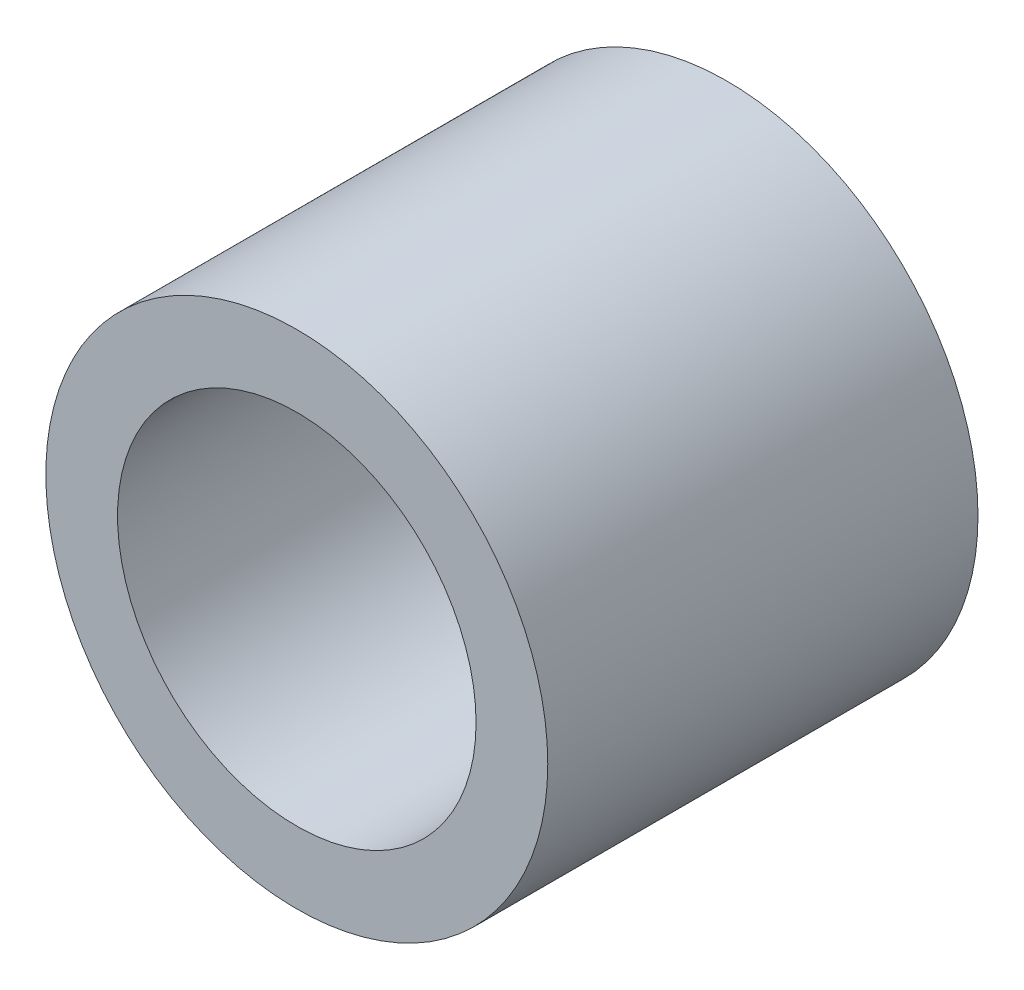
SolidWorks part; units mm, degrees
ref_plane "前视基准面" through (0, 0, 0) normal (0, 0, 1) x (1, 0, 0)
ref_plane "上视基准面" through (0, 0, 0) normal (0, 1, 0) x (1, 0, 0)
ref_plane "右视基准面" through (0, 0, 0) normal (1, 0, 0) x (0, 0, -1)
other "Configuration Table"
sketch "草图1" plane through (0, 0, 0) normal (0, 0, 1) x (1, 0, 0)
  circle A0 centre (0, 0) radius 5
  circle A1 centre (0, 0) radius 7
  dimension "D1" = 10
  dimension "D2" = 14
extrude "凸台-拉伸1" add sketch "草图1" along normal blind 12
